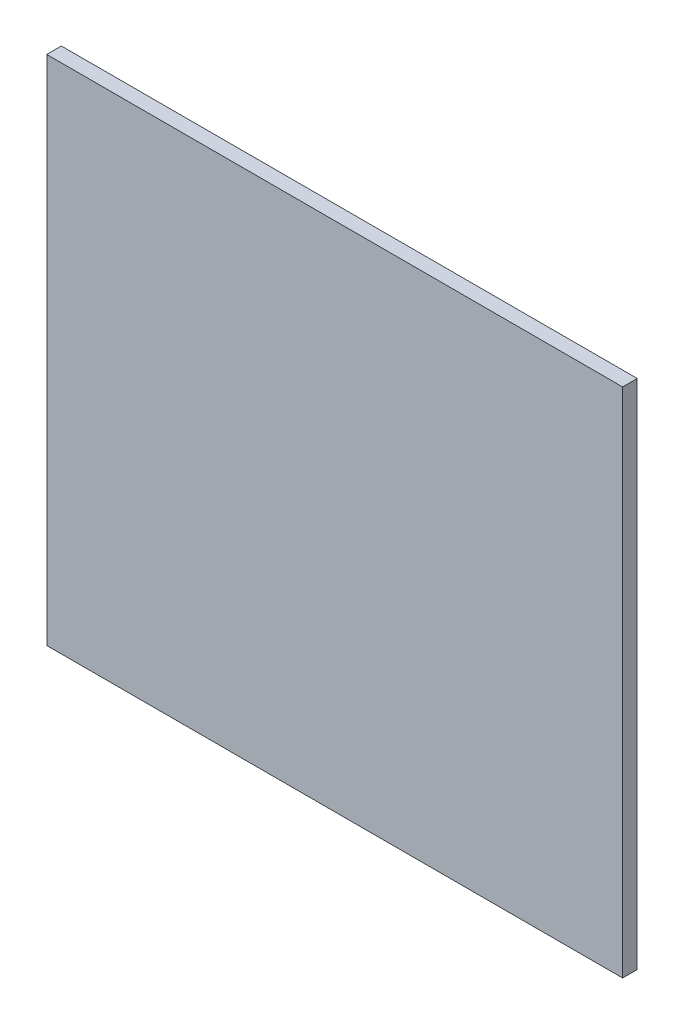
SolidWorks part; units mm, degrees
ref_plane "Front" through (0, 0, 0) normal (0, 0, 1) x (1, 0, 0)
ref_plane "Top" through (0, 0, 0) normal (0, 1, 0) x (1, 0, 0)
ref_plane "Right" through (0, 0, 0) normal (1, 0, 0) x (0, 0, -1)
sketch "Sketch1" plane through (0, 0, 0) normal (0, 0, 1) x (1, 0, 0)
  line L1 (0, 0) -> (-80.01, 0)
  line L2 (0, 0) -> (0, 71.12)
  line L3 (0, 71.12) -> (-80.01, 71.12)
  line L4 (-80.01, 0) -> (-80.01, 71.12)
  dimension "D1" = 71.12
  dimension "D2" = 80.01
extrude "Boss-Extrude1" add sketch "Sketch1" along normal blind 2.032
sketch "Sketch2" plane through (0, 0, 2.032) normal (0, 0, 1) x (1, 0, 0)
  line L0 (-80.01, 35.56) -> (0, 35.56) construction
  line L1 (-55.88, 58.42) -> (-53.34, 58.42) construction
  line L2 (-55.88, 58.42) -> (-55.88, 12.7) construction
  line L3 (-55.88, 12.7) -> (-53.34, 12.7) construction
  line L4 (-53.34, 58.42) -> (-53.34, 12.7) construction
  line L5 (-80.01, 71.12) -> (-80.01, 0) construction
  line L6 (0, 0) -> (0, 71.12) construction
  point P10 (-55.88, 35.56)
  dimension "D1" = 2.54
  dimension "D2" = 45.72
  dimension "D3" = 24.13
